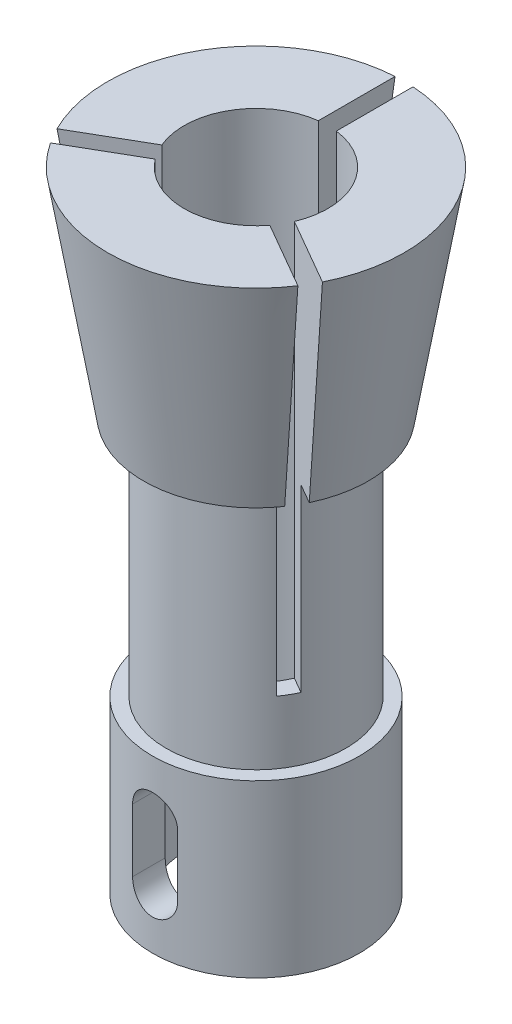
SolidWorks part; units mm, degrees
material "AISI 4130 Steel, annealed at 865C"
ref_plane "Front Plane" through (0, 0, 0) normal (0, 0, 1) x (1, 0, 0)
ref_plane "Top Plane" through (0, 0, 0) normal (0, 1, 0) x (1, 0, 0)
ref_plane "Right Plane" through (0, 0, 0) normal (1, 0, 0) x (0, 0, -1)
sketch "Sketch1" plane through (0, 0, 0) normal (0, 0, 1) x (1, 0, 0)
  line L0 (8, 0) -> (11.5, 0)
  line L1 (11.5, 0) -> (11.5, 19)
  line L2 (11.5, 19) -> (10, 19)
  line L3 (10, 19) -> (10, 46)
  line L4 (10, 46) -> (12.5, 46)
  line L5 (12.5, 46) -> (16.5, 70)
  line L6 (16.5, 70) -> (8, 70)
  line L8 (8, 70) -> (8, 0)
  line L9 (0, 72.6358) -> (0, -3.4207) construction
  dimension "D1" = 70
  dimension "D2" = 8
  dimension "D3" = 19
  dimension "D4" = 24
  dimension "D5" = 16.5
  dimension "D6" = 12.5
  dimension "D7" = 11.5
  dimension "D8" = 10
revolve "Revolve1" add sketch "Sketch1" angle 360 about L9
sketch "Sketch2" plane through (0, 0, 0) normal (0, 0, 1) x (1, 0, 0)
  line L0 (0, 13) -> (0, 6) construction
  line L1 (2.5, 13) -> (2.5, 6)
  line L2 (-2.5, 13) -> (-2.5, 6)
  arc A0 (2.5, 13) -> (-2.5, 13) centre (0, 13) ccw
  arc A1 (-2.5, 6) -> (2.5, 6) centre (0, 6) ccw
  point P3 (0, 9.5)
  dimension "D1" = 2.5
  dimension "D2" = 7
  dimension "D3" = 9.5
extrude "Cut-Extrude1" cut sketch "Sketch2" against normal through all both and the other way through all
sketch "Sketch3" plane through (0, 70, 0) normal (0, 1, 0) x (1, 0, 0)
  line L1 (-1, 22.1718) -> (1, 22.1718)
  line L2 (-1, 22.1718) -> (-1, 5.1718)
  line L3 (-1, 5.1718) -> (1, 5.1718)
  line L4 (1, 22.1718) -> (1, 5.1718)
  dimension "D1" = 2
  dimension "D2" = 1
  dimension "D3" = 17
extrude "Cut-Extrude2" cut sketch "Sketch3" against normal blind 44
pattern_circular "CirPattern1" count 3 over 360 about axis through (0, 0, 0) along (0, 1, 0) of "Cut-Extrude2"
